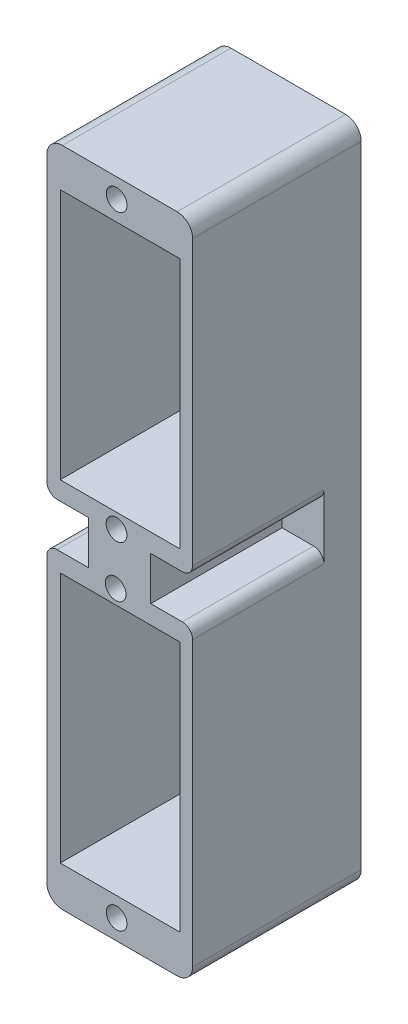
SolidWorks part; units mm, degrees
ref_plane "Front Plane" through (0, 0, 0) normal (0, 0, 1) x (1, 0, 0)
ref_plane "Top Plane" through (0, 0, 0) normal (0, 1, 0) x (1, 0, 0)
ref_plane "Right Plane" through (0, 0, 0) normal (1, 0, 0) x (0, 0, -1)
other "Graphic1"
other "object_1 (Open) -1"
ref_plane "Plane1" through (0, 0, 30) normal (0, 0, 1) x (1, 0, 0)
sketch "Sketch4" plane through (0, 0, 30) normal (0, 0, 1) x (1, 0, 0)
  line L1 (-189.837, 275.5472) -> (-175.737, 275.5472)
  line L2 (-189.837, 275.5472) -> (-189.837, 211.5472)
  line L3 (-189.837, 211.5472) -> (-175.737, 211.5472)
  line L4 (-175.737, 275.5472) -> (-175.737, 211.5472)
  dimension "D1" = 64
  dimension "D2" = 14.1
extrude "Boss-Extrude1" add sketch "Sketch4" along normal blind 16.3
fillet "Fillet1" radius 1.5 4 edges at (-189.837, 275.5472, 38.15) (-175.737, 275.5472, 38.15) (-189.837, 211.5472, 38.15) (-175.737, 211.5472, 38.15)
sketch "Sketch5" plane through (0, 0, 46.3) normal (0, 0, 1) x (1, 0, 0)
  line L0 (-177.237, 275.5472) -> (-188.337, 275.5472) construction
  line L1 (-188.537, 271.7472) -> (-176.937, 271.7472)
  line L2 (-188.537, 271.7472) -> (-188.537, 247.4472)
  line L3 (-188.537, 247.4472) -> (-176.937, 247.4472)
  line L4 (-176.937, 271.7472) -> (-176.937, 247.4472)
  line L5 (-175.737, 213.0472) -> (-175.737, 274.0472) construction
  line L6 (-188.337, 211.5472) -> (-177.237, 211.5472) construction
  line L7 (-188.537, 239.6472) -> (-176.937, 239.6472)
  line L8 (-188.537, 239.6472) -> (-188.537, 215.3472)
  line L9 (-188.537, 215.3472) -> (-176.937, 215.3472)
  line L10 (-176.937, 239.6472) -> (-176.937, 215.3472)
  point P6 (-182.787, 275.5472)
  dimension "D1" = 11.6
  dimension "D2" = 24.3
  dimension "D3" = 3.8
  dimension "D4" = 1.2
  dimension "D5" = 24.3
  dimension "D6" = 3.8
extrude "Cut-Extrude1" cut sketch "Sketch5" against normal blind 16.3
sketch "Sketch6" plane through (0, 0, 46.3) normal (0, 0, 1) x (1, 0, 0)
  line L0 (-189.837, 274.0472) -> (-189.837, 213.0472) construction
  line L1 (-185.787, 245.6472) -> (-189.837, 245.6472)
  line L2 (-185.787, 245.6472) -> (-185.787, 241.4472)
  line L3 (-185.787, 241.4472) -> (-189.837, 241.4472)
  line L4 (-189.837, 245.6472) -> (-189.837, 241.4472)
  line L5 (-175.737, 213.0472) -> (-175.737, 274.0472) construction
  line L6 (-179.787, 245.6472) -> (-175.737, 245.6472)
  line L7 (-179.787, 245.6472) -> (-179.787, 241.4472)
  line L8 (-179.787, 241.4472) -> (-175.737, 241.4472)
  line L9 (-175.737, 245.6472) -> (-175.737, 241.4472)
  line L10 (-188.537, 247.4472) -> (-176.937, 247.4472) construction
  line L11 (-176.937, 239.6472) -> (-188.537, 239.6472) construction
  dimension "D1" = 6
  dimension "D2" = 1.8
  dimension "D3" = 1.8
extrude "Cut-Extrude2" cut sketch "Sketch6" against normal blind 12.7
fillet "Fillet2" radius 1 4 edges at (-175.737, 241.4472, 39.95) (-175.737, 245.6472, 39.95) (-189.837, 241.4472, 39.95) (-189.837, 245.6472, 39.95)
sketch "Sketch7" plane through (0, 0, 46.3) normal (0, 0, 1) x (1, 0, 0)
  circle A0 centre (-183.0861, 273.6519) radius 1
  circle A1 centre (-183.0861, 213.4755) radius 1
  circle A2 centre (-183.0989, 246.016) radius 1
  circle A3 centre (-183.182, 241.0167) radius 1
  point P8 (-183.182, 241.0167)
  dimension "D1" = 5
extrude "Cut-Extrude3" cut sketch "Sketch7" against normal blind 16.3
